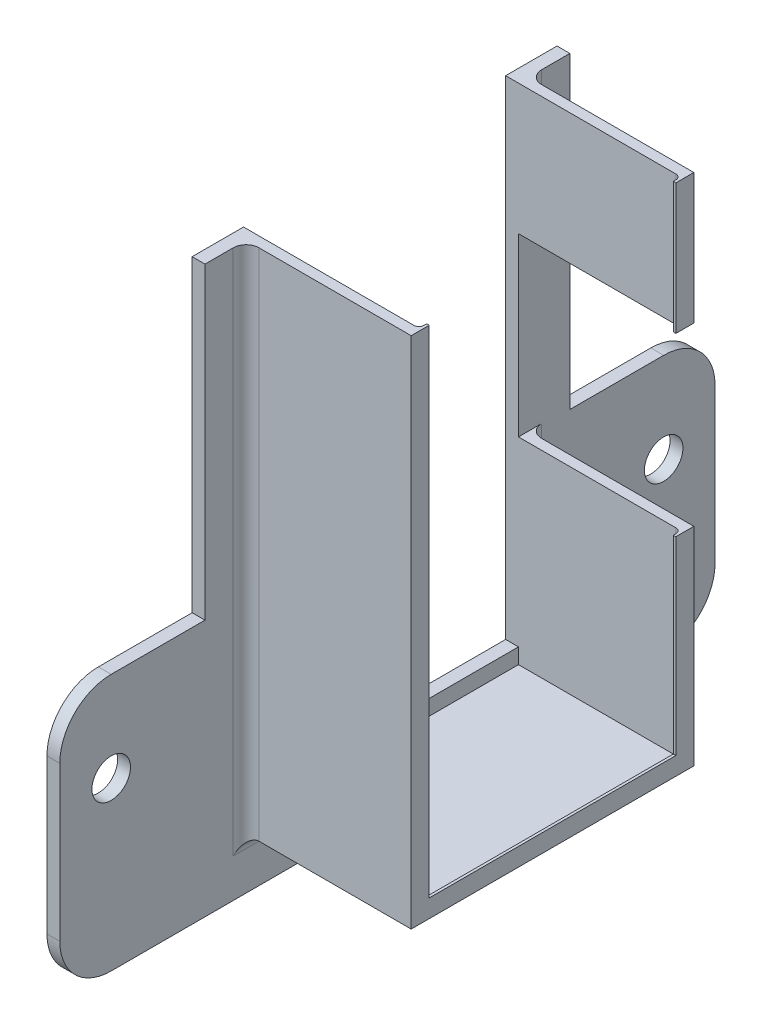
SolidWorks part; units mm, degrees
ref_plane "Front Plane" through (0, 0, 0) normal (0, 0, 1) x (1, 0, 0)
ref_plane "Top Plane" through (0, 0, 0) normal (0, 1, 0) x (1, 0, 0)
ref_plane "Right Plane" through (0, 0, 0) normal (1, 0, 0) x (0, 0, -1)
sketch "Sketch1" plane through (-75.5364, 0, 0) normal (1, 0, 0) x (0, 0, -1)
  line L12 (0, 80.9) -> (0, 12.2026) construction
  line L13 (-25.5, 40.4) -> (-10.2, 40.4) construction
  line L14 (-25.5, 40.4) -> (-25.5, 54.4)
  line L15 (-25.5, 54.4) -> (-10.2, 54.4) construction
  line L16 (-10.2, 40.4) -> (-10.2, 54.4)
  line L19 (-25.5, 34.4) -> (25.5, 34.4)
  line L20 (-25.5, 40.4) -> (-25.5, 34.4)
  line L21 (-10.2, 40.4) -> (10.2, 40.4)
  line L22 (-10.2, 54.4) -> (-10.2, 78.4)
  line L23 (-25.5, 54.4) -> (-14.2, 54.4)
  line L24 (-14.2, 54.4) -> (-14.2, 78.4)
  line L25 (-14.2, 78.4) -> (-10.2, 78.4)
  line L26 (25.5, 54.4) -> (10.2, 54.4) construction
  line L27 (25.5, 40.4) -> (10.2, 40.4) construction
  line L28 (14.2, 78.4) -> (10.2, 78.4)
  line L29 (14.2, 54.4) -> (14.2, 78.4)
  line L30 (25.5, 54.4) -> (14.2, 54.4)
  line L31 (10.2, 54.4) -> (10.2, 78.4)
  line L33 (25.5, 40.4) -> (25.5, 34.4)
  line L35 (10.2, 40.4) -> (10.2, 54.4)
  line L36 (25.5, 40.4) -> (25.5, 54.4)
  line L37 (-10.1, 39.3) -> (-10.1, 83.5) construction
  circle A0 centre (0, 72.9) radius 8 construction
  point P0 (-21.5, 47.4)
  point P11 (0, 40.4)
  point P14 (21.5, 47.4)
  point P21 (0, 34.4)
  point P27 (0, 40.4)
  point P28 (0, 34.4)
  dimension "D1" = 0.1
  dimension "D2" = 14
  dimension "D3" = 6
  dimension "D5" = 4
  dimension "D6" = 24
  dimension "D4" = 4
  dimension "D7" = 7
extrude "Boss-Extrude1" add sketch "Sketch1" along normal blind 1
fillet "Fillet2" radius 4 4 edges at (-75.0364, 34.4, 25.5) (-75.0364, 54.4, 25.5) (-75.0364, 34.4, -25.5) (-75.0364, 54.4, -25.5)
sketch "Sketch2" plane through (-74.5364, 0, 0) normal (1, 0, 0) x (0, 0, -1)
  line L1 (-10.2, 38.4) -> (10.2, 38.4)
  line L2 (-10.2, 38.4) -> (-10.2, 39.2)
  line L3 (-10.2, 39.2) -> (10.2, 39.2)
  line L4 (10.2, 38.4) -> (10.2, 39.2)
  line L10 (10.1, 39.3) -> (-10.1, 39.3) construction
  line L13 (-10.1, 39.3) -> (-10.1, 83.5) construction
  line L14 (10.1, 83.5) -> (10.1, 39.3) construction
  dimension "D1" = 0.8
  dimension "D2" = 0.1
  dimension "D3" = 0.1
  dimension "D4" = 0.1
extrude "Boss-Extrude2" add sketch "Sketch2" along normal up to surface (12.25 mm away)
sketch "Sketch3" plane through (-74.5364, 0, 0) normal (1, 0, 0) x (0, 0, -1)
  line L0 (10.2, 38.4) -> (-10.2, 38.4) construction
  line L1 (-10.2, 78.4) -> (-11, 78.4)
  line L2 (-10.2, 78.4) -> (-10.2, 38.4)
  line L3 (-10.2, 38.4) -> (-11, 38.4)
  line L4 (-11, 78.4) -> (-11, 38.4)
  dimension "D1" = 0.8
extrude "Boss-Extrude3" add sketch "Sketch3" along normal up to surface (12.25 mm away)
sketch "Sketch5" plane through (-74.5364, 0, 0) normal (1, 0, 0) x (0, 0, -1)
  line L0 (7.56, 55.05) -> (10.1, 55.05) construction
  line L1 (10.2, 38.4) -> (11, 38.4)
  line L2 (10.2, 38.4) -> (10.2, 54.55)
  line L3 (10.2, 54.55) -> (11, 54.55)
  line L4 (11, 38.4) -> (11, 54.55)
  line L5 (10.1, 67.75) -> (7.56, 67.75) construction
  line L6 (10.2, 78.4) -> (11, 78.4)
  line L7 (10.2, 78.4) -> (10.2, 68.25)
  line L8 (10.2, 68.25) -> (11, 68.25)
  line L9 (11, 78.4) -> (11, 68.25)
  dimension "D1" = 0.5
  dimension "D2" = 0.8
  dimension "D3" = 0.5
  dimension "D4" = 0.8
extrude "Boss-Extrude4" add sketch "Sketch5" along normal up to surface (12.25 mm away)
fillet "Fillet3" radius 1 4 edges at (-74.5364, 58.4, 11) (-74.5364, 38.4, 0) (-74.5364, 46.475, -11) (-74.5364, 73.325, -11)
sketch "Sketch6" plane through (-62.2864, 0, 0) normal (1, 0, 0) x (0, 0, -1)
  line L0 (-11, 38.4) -> (11, 38.4) construction
  line L1 (11, 38.4) -> (11, 54.55) construction
  line L2 (11, 54.55) -> (10.2, 54.55) construction
  line L3 (10.2, 54.55) -> (10.2, 39.2) construction
  line L4 (10.2, 39.2) -> (-10.2, 39.2) construction
  line L5 (-10.2, 39.2) -> (-10.2, 78.4) construction
  line L6 (-10.2, 78.4) -> (-11, 78.4) construction
  line L7 (-11, 78.4) -> (-11, 38.4) construction
  line L8 (10.2, 68.25) -> (11, 68.25) construction
  line L9 (11, 68.25) -> (11, 78.4) construction
  line L10 (11, 78.4) -> (10.2, 78.4) construction
  line L11 (10.2, 78.4) -> (10.2, 68.25) construction
  line L12 (-11, 38.4) -> (11, 38.4)
  line L13 (11, 38.4) -> (11, 54.55)
  line L14 (11, 54.55) -> (10.2, 54.55)
  line L15 (10.2, 54.55) -> (10.2, 39.2)
  line L16 (10.2, 39.2) -> (-10.2, 39.2)
  line L17 (-10.2, 39.2) -> (-10.2, 78.4)
  line L18 (-10.2, 78.4) -> (-11, 78.4)
  line L19 (-11, 78.4) -> (-11, 38.4)
  line L20 (10.2, 68.25) -> (11, 68.25)
  line L21 (11, 68.25) -> (11, 78.4)
  line L22 (11, 78.4) -> (10.2, 78.4)
  line L23 (10.2, 78.4) -> (10.2, 68.25)
extrude "Boss-Extrude5" add sketch "Sketch6" along normal blind 0.6
sketch "Sketch7" plane through (-61.6864, 0, 0) normal (1, 0, 0) x (0, 0, -1)
  line L0 (10.2, 78.4) -> (10.2, 68.25) construction
  line L8 (10.2, 54.55) -> (10.2, 39.2) construction
  line L9 (10.2, 39.2) -> (-10.2, 39.2) construction
  line L10 (-10.2, 39.2) -> (-10.2, 78.4) construction
  line L12 (10.2, 78.4) -> (10.2, 68.25)
  line L20 (10.2, 54.55) -> (10.2, 39.2)
  line L21 (10.2, 39.2) -> (-10.2, 39.2)
  line L22 (-10.2, 39.2) -> (-10.2, 78.4)
extrude "Extrude-Thin1" add sketch "Sketch7" against normal blind 0.2 thin
fillet "Fillet4" radius 0.4 4 edges at (-61.8864, 58.8, 10.2) (-61.8864, 39.2, 0) (-61.8864, 46.875, -10.2) (-61.8864, 73.325, -10.2)
sketch "Sketch8" plane through (0, 0, -11) normal (0, 0, -1) x (-1, 0, 0)
  line L0 (73.5364, 54.55) -> (74.5364, 54.55)
  line L1 (74.5364, 54.55) -> (74.5364, 68.25)
  line L2 (74.5364, 68.25) -> (61.6864, 68.25)
  line L3 (61.6864, 68.25) -> (73.5364, 68.25) construction
  line L4 (61.6864, 68.25) -> (61.6864, 54.55)
  line L5 (61.6864, 54.55) -> (74.5364, 54.55)
  line L7 (74.5364, 37.4) -> (74.5364, 78.4) construction
sketch "Sketch9" plane through (-74.5364, 0, 0) normal (1, 0, 0) x (0, 0, -1)
  point P0 (17, 45.1441)
  point P3 (-17, 46.1934)
sketch "Sketch11" plane through (-74.5364, 0, 0) normal (1, 0, 0) x (0, 0, -1)
  point P0 (21.5, 47.4)
  point P3 (-21.5, 47.4)
hole_wizard "Ø3.0mm Dowel Hole2" positions "Sketch11" profile "Sketch12" hole size "Ø3.0" standard "ANSI Metric" end condition up to next
sketch "Sketch12" plane through (-74.5364, 47.4, -21.5) normal (0, 1, 0) x (0, 0, -1)
  line L0 (0, 0) -> (0, 1)
  line L1 (0, 1) -> (1.5, 1)
  line L2 (1.5, 1) -> (1.5, 0)
  line L5 (1.5, 0) -> (0, 0)
  line L11 (0, -6.35) -> (0, 107.95) construction
  dimension "Thru Hole Dia." = 3
  dimension "Thru Hole Depth" = 1
